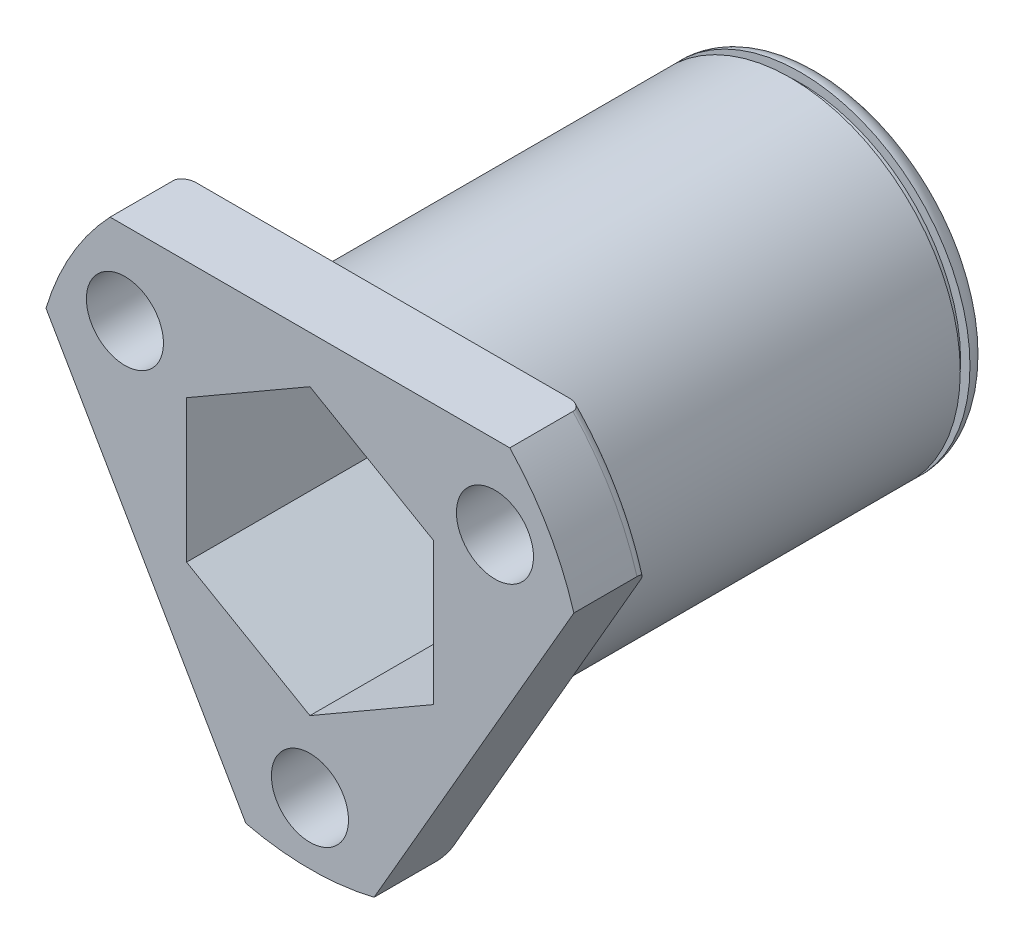
SolidWorks part; units mm, degrees
material "6061 Alloy"
ref_plane "Front Plane" through (0, 0, 0) normal (0, 0, 1) x (1, 0, 0)
ref_plane "Top Plane" through (0, 0, 0) normal (0, 1, 0) x (1, 0, 0)
ref_plane "Right Plane" through (0, 0, 0) normal (1, 0, 0) x (0, 0, -1)
sketch "Sketch1" plane through (0, 0, 0) normal (1, 0, 0) x (0, 0, -1)
  line L0 (0, 0) -> (55, 0)
  line L1 (55, 0) -> (55, 15.4625)
  line L2 (53, 17.4625) -> (11, 17.4625)
  line L3 (10, 18.4625) -> (10, 27.35)
  line L4 (9, 28.35) -> (1, 28.35)
  line L5 (0, 27.35) -> (0, 0)
  line L6 (53, 17.4625) -> (53, 16.5)
  line L7 (53, 16.5) -> (52, 16.5)
  line L8 (52, 16.5) -> (52, 17.4625)
  arc A0 (55, 15.4625) -> (53, 17.4625) centre (53, 15.4625) ccw
  arc A1 (10, 27.35) -> (9, 28.35) centre (9, 27.35) ccw
  arc A2 (1, 28.35) -> (0, 27.35) centre (1, 27.35) ccw
  arc A3 (11, 17.4625) -> (10, 18.4625) centre (11, 18.4625) cw
  point P11 (10, 28.35)
  point P14 (0, 28.35)
  dimension "D5" = 2
  dimension "D6" = 1
  dimension "D1" = 17.4625
  dimension "D2" = 28.35
  dimension "D3" = 10
  dimension "D4" = 55
  dimension "D7" = 1
  dimension "D8" = 16.5
revolve "Revolve1" add sketch "Sketch1" angle 360 about L0
sketch "Sketch2" plane through (0, 0, 0) normal (0, 0, 1) x (1, 0, 0)
  line L1 (0, 14.6647) -> (-12.7, 7.3323)
  line L2 (-12.7, 7.3323) -> (-12.7, -7.3323)
  line L3 (-12.7, -7.3323) -> (0, -14.6647)
  line L4 (0, -14.6647) -> (12.7, -7.3323)
  line L5 (12.7, -7.3323) -> (12.7, 7.3323)
  line L6 (12.7, 7.3323) -> (0, 14.6647)
  line L7 (-19.05, 10.9985) -> (0, -21.997)
  line L8 (0, -21.997) -> (19.05, 10.9985)
  line L9 (19.05, 10.9985) -> (-19.05, 10.9985)
  circle A0 centre (0, 0) radius 12.7 construction
  circle A1 centre (0, 0) radius 21.997 construction
  circle A2 centre (-19.05, 10.9985) radius 3.9688
  circle A3 centre (19.05, 10.9985) radius 3.9688
  circle A4 centre (0, -21.997) radius 3.9688
  dimension "D1" = 25.4
  dimension "D3" = 7.9375
  dimension "D4" = 7.9375
  dimension "D5" = 7.9375
  dimension "D2" = 38.1
extrude "Cut-Extrude1" cut sketch "Sketch2" against normal through all contours L6 L9 L1 L2 L7 L3 L4 L8 L5 | L9 L6 L1 | L7 L2 L3 | L8 L4 L5 | L9 A2 L7 | L7 A2 L9 | L8 A3 L9 | L9 A3 L8 | L7 A4 L8 | L8 A4 L7
sketch "Sketch3" plane through (0, 0, 0) normal (1, 0, 0) x (0, 0, -1)
  line L0 (0, 7.3323) -> (0, 14.6647) construction
  line L1 (0, 7.3323) -> (0, 14.6647)
  line L2 (0, 14.6647) -> (3.5, 11.1647)
  line L3 (3.5, 11.1647) -> (0, 11.1647)
  line L4 (55, 7.3323) -> (55, 14.6647) construction
  line L5 (55, 7.3323) -> (55, 14.6647)
  line L6 (55, 14.6647) -> (51.5, 11.1647)
  line L7 (51.5, 11.1647) -> (55, 11.1647)
  line L8 (55, 0) -> (0, 0) construction
  dimension "D1" = 3.5
  dimension "D2" = 45
  dimension "D3" = 3.5
  dimension "D4" = 45
revolve "Cut-Revolve2" cut sketch "Sketch3" angle 360 about L8
sketch "Sketch4" plane through (0, 0, -10) normal (0, 0, -1) x (-1, 0, 0)
  line L0 (0, 0) -> (0, -39) construction
  line L1 (0, 0) -> (-33.775, 19.5) construction
  line L2 (0, 0) -> (33.775, 19.5) construction
  line L3 (0, -39) -> (33.775, 19.5)
  line L4 (33.775, 19.5) -> (-33.775, 19.5)
  line L5 (-33.775, 19.5) -> (0, -39)
  line L7 (-45.5301, 42.6695) -> (45.5301, 42.6695)
  line L8 (-45.5301, 42.6695) -> (-45.5301, -42.6695)
  line L9 (-45.5301, -42.6695) -> (45.5301, -42.6695)
  line L10 (45.5301, 42.6695) -> (45.5301, -42.6695)
  line L11 (-45.5301, 42.6695) -> (45.5301, -42.6695) construction
  line L12 (-45.5301, -42.6695) -> (45.5301, 42.6695) construction
  point P7 (0, 0)
  dimension "D1" = 3
extrude "Cut-Extrude2" cut sketch "Sketch4" against normal blind 10
sketch "Sketch5" plane through (0, 0, 0) normal (0, 0, 1) x (1, 0, 0)
  line L1 (29.5637, -29.7119) -> (-29.5637, -29.7119)
  line L2 (29.5637, -29.7119) -> (29.5637, 29.7119)
  line L3 (29.5637, 29.7119) -> (-29.5637, 29.7119)
  line L4 (-29.5637, -29.7119) -> (-29.5637, 29.7119)
  line L5 (29.5637, -29.7119) -> (-29.5637, 29.7119) construction
  line L6 (29.5637, 29.7119) -> (-29.5637, -29.7119) construction
  point P0 (0, 0)
extrude "Cut-Extrude3" cut sketch "Sketch5" against normal blind 2.5
